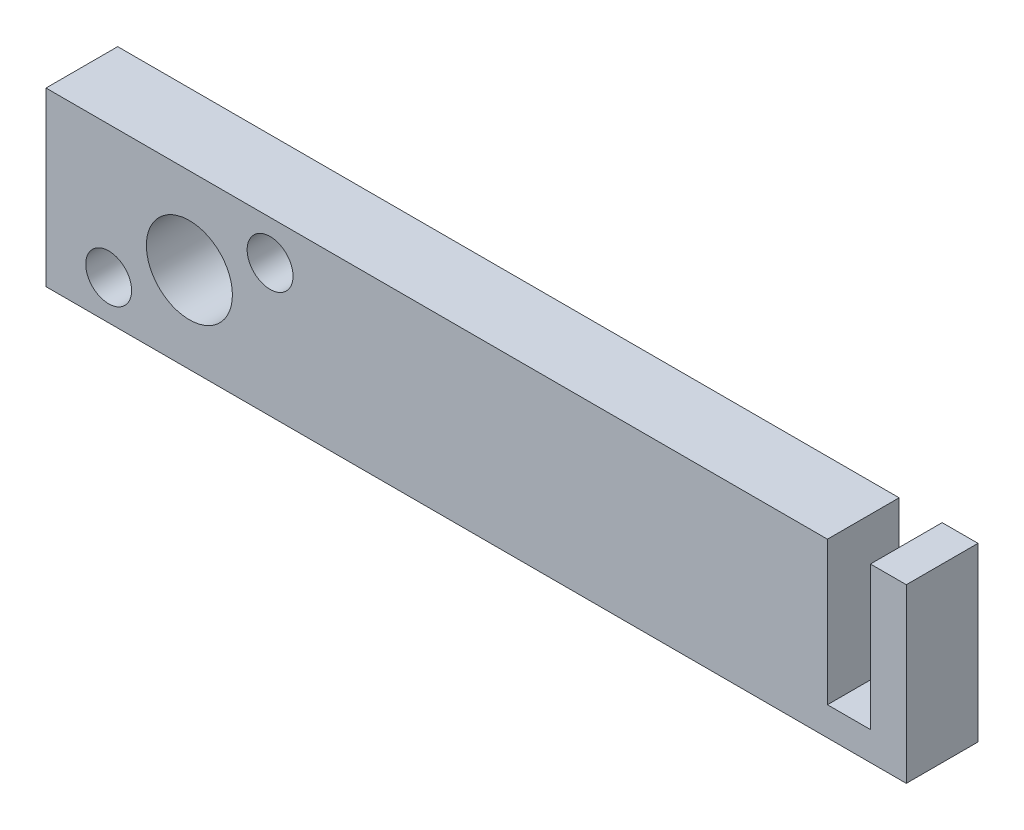
SolidWorks part; units mm, degrees
ref_plane "正面" through (0, 0, 0) normal (0, 0, 1) x (1, 0, 0)
ref_plane "平面" through (0, 0, 0) normal (0, 1, 0) x (1, 0, 0)
ref_plane "右側面" through (0, 0, 0) normal (1, 0, 0) x (0, 0, -1)
sketch "ｽｹｯﾁ1" plane through (0, 0, 0) normal (0, 0, 1) x (1, 0, 0)
  line L0 (0, 0) -> (10, 0)
  line L1 (0, 0) -> (5.6292, 3.25)
  line L2 (0, 0) -> (-5.6292, -3.25)
  line L3 (0, 0) -> (0, -6)
  line L4 (0, -6) -> (50, -6)
  line L5 (50, -6) -> (50, 6)
  line L6 (50, 6) -> (47.5, 6)
  line L7 (-10, 6) -> (-10, -6)
  line L8 (-10, -6) -> (0, -6)
  line L9 (50, 6) -> (47.5, 6)
  line L10 (47.5, 6) -> (47.5, -4)
  line L11 (47.5, -4) -> (44.5, -4)
  line L12 (44.5, -4) -> (44.5, 6)
  line L13 (44.5, 6) -> (-10, 6)
  circle A0 centre (0, 0) radius 3
  circle A1 centre (5.6292, 3.25) radius 1.6
  circle A2 centre (-5.6292, -3.25) radius 1.6
  dimension "D4" = 6
  dimension "D5" = 3.2
  dimension "D6" = 3.2
  dimension "D1" = 10
  dimension "D2" = 6.5
  dimension "D3" = 6.5
  dimension "D7" = 6
  dimension "D8" = 50
  dimension "D9" = 12
  dimension "D10" = 60
  dimension "D11" = 2.5
  dimension "D12" = 10
  dimension "D13" = 3
extrude "ﾎﾞｽ - 押し出し1" add sketch "ｽｹｯﾁ1" along normal blind 5
sketch "ｽｹｯﾁ2" plane through (0, 0, 5) normal (0, 0, 1) x (1, 0, 0)
  line L0 (0, 0) -> (44.5, 0)
  line L1 (44.5, -4) -> (44.5, 6) construction
  line L2 (44.5, 0) -> (44.5, -4)
  line L3 (44.5, 0) -> (46, 0)
  dimension "D1" = 1.5
